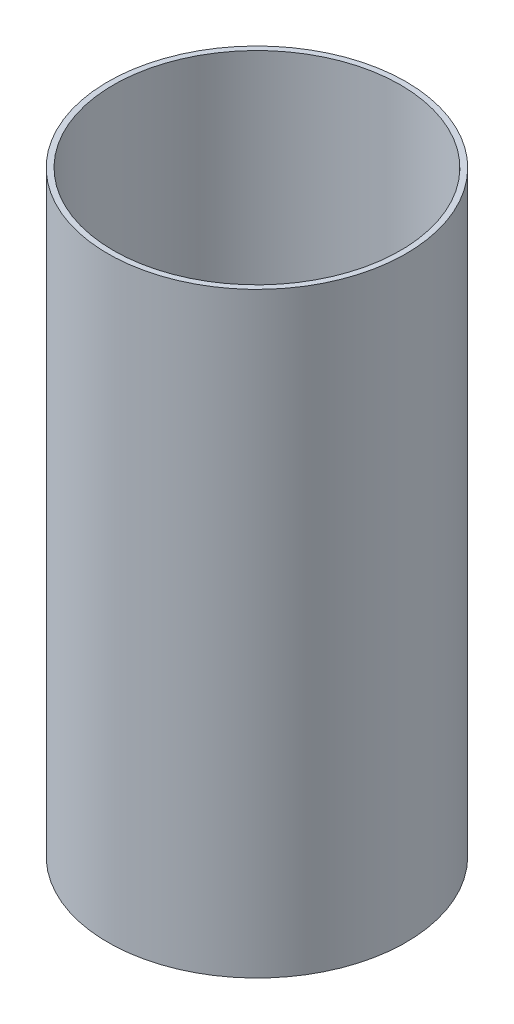
SolidWorks part; units mm, degrees
material "E-Glass Fiber"
ref_plane "Front Plane" through (0, 0, 0) normal (0, 0, 1) x (1, 0, 0)
ref_plane "Top Plane" through (0, 0, 0) normal (0, 1, 0) x (1, 0, 0)
ref_plane "Right Plane" through (0, 0, 0) normal (1, 0, 0) x (0, 0, -1)
sketch "Coupler Profile" plane through (0, 0, 0) normal (0, 1, 0) x (1, 0, 0)
  circle A0 centre (0, 0) radius 73.3425
  circle A1 centre (0, 0) radius 76.1746
  dimension "D1" = 146.685
  dimension "D2" = 152.3492
extrude "Coupler Body" add sketch "Coupler Profile" along normal blind 304.8
equation "\"Length\"= 12"
equation "\"Outer Diameter\"= 5.998"
equation "\"Inner Diameter\"= 5.775"
equation "\"Wall Thickness\"= 0.111"
equation "\"D1@Coupler Profile\"=\"Inner Diameter\""
equation "\"D2@Coupler Profile\"=\"Outer Diameter\""
equation "\"D1@Coupler Body\"=\"Length\""
